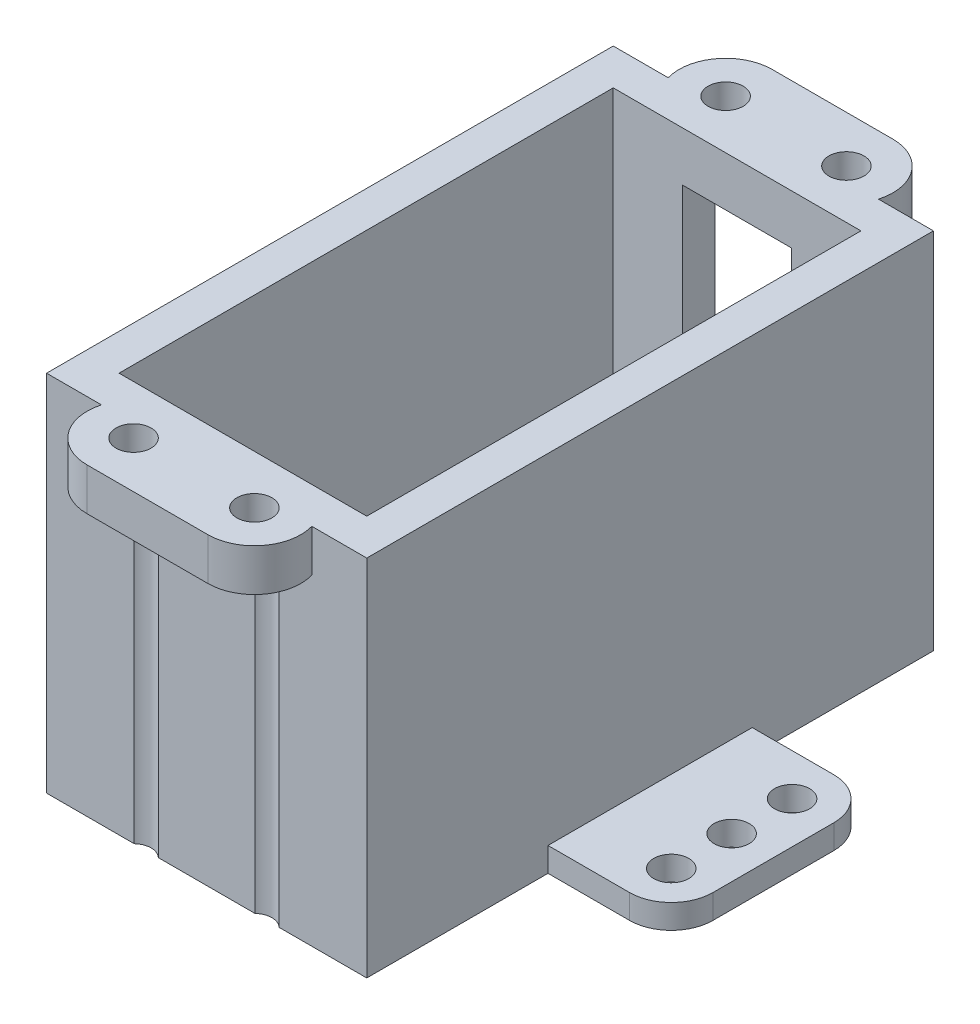
SolidWorks part; units mm, degrees
ref_plane "Alzado" through (0, 0, 0) normal (0, 0, 1) x (1, 0, 0)
ref_plane "Planta" through (0, 0, 0) normal (0, 1, 0) x (1, 0, 0)
ref_plane "Vista lateral" through (0, 0, 0) normal (1, 0, 0) x (0, 0, -1)
sketch "Croquis2" plane through (0, 0, 0) normal (0, 1, 0) x (1, 0, 0)
  line L0 (-10.8387, 0) -> (0, 0) construction
  line L1 (0, 5) -> (0, -5) construction
  line L2 (-23.45, 5) -> (-23.45, -5)
  line L3 (-13.25, -23.45) -> (13.25, -23.45)
  line L4 (-13.25, -23.45) -> (-13.25, -8.45)
  line L5 (-13.25, 23.45) -> (13.25, 23.45)
  line L6 (13.25, -23.45) -> (13.25, -8.45)
  line L7 (-13.25, -23.45) -> (13.25, 23.45) construction
  line L8 (-13.25, 23.45) -> (13.25, -23.45) construction
  line L9 (-20, -8.45) -> (-13.25, -8.45)
  line L10 (20, -8.45) -> (13.25, -8.45)
  line L11 (23.45, -5) -> (23.45, 5)
  line L12 (20, 8.45) -> (13.25, 8.45)
  line L13 (-20, 8.45) -> (-13.25, 8.45)
  line L14 (-13.25, 8.45) -> (-13.25, 23.45)
  line L15 (13.25, 8.45) -> (13.25, 23.45)
  circle A0 centre (-20, 5) radius 1.45
  circle A1 centre (-20, -5) radius 1.45
  circle A2 centre (20, -5) radius 1.45
  circle A3 centre (20, 5) radius 1.45
  arc A4 (-20, 8.45) -> (-23.45, 5) centre (-20, 5) ccw
  arc A5 (-20, -8.45) -> (-23.45, -5) centre (-20, -5) cw
  arc A6 (20, 8.45) -> (23.45, 5) centre (20, 5) cw
  arc A7 (20, -8.45) -> (23.45, -5) centre (20, -5) ccw
  circle A8 centre (-20, 0) radius 1.45
  circle A9 centre (-20, 5) radius 3.45 construction
  circle A10 centre (-20, -5) radius 3.45 construction
  circle A11 centre (20, 5) radius 3.45 construction
  circle A12 centre (20, -5) radius 3.45 construction
  circle A13 centre (20, 0) radius 1.45
  point P18 (-16.55, -5)
  point P20 (23.45, 5)
  point P22 (23.45, -5)
  point P37 (-16.55, 5)
  dimension "D1" = 2.9
  dimension "D2" = 5
  dimension "D3" = 20
  dimension "D7" = 2.9
  dimension "D8" = 20
  dimension "D4" = 26.5
  dimension "D5" = 46.9
  dimension "D6" = 2
extrude "Saliente-Extruir1" add sketch "Croquis2" along normal blind 2
sketch "Croquis3" plane through (0, 2, 0) normal (0, 1, 0) x (1, 0, 0)
  line L0 (-10.25, 20.45) -> (-10.25, -20.45)
  line L1 (-13.25, 23.45) -> (13.25, 23.45)
  line L2 (-13.25, 23.45) -> (-13.25, -23.45)
  line L3 (-13.25, -23.45) -> (13.25, -23.45)
  line L4 (13.25, 23.45) -> (13.25, -23.45)
  line L5 (-10.25, -20.45) -> (10.25, -20.45)
  line L6 (10.25, 20.45) -> (10.25, -20.45)
  line L7 (-10.25, 20.45) -> (10.25, 20.45)
  dimension "D1" = 3
extrude "Saliente-Extruir2" add sketch "Croquis3" along normal blind 28.1
sketch "Croquis4" plane through (0, 30.1, 0) normal (0, 1, 0) x (1, 0, 0)
  line L0 (0, 0) -> (0, 28.3845) construction
  line L1 (0, 0) -> (26.4868, 0) construction
  line L2 (-5, 28.3482) -> (5, 28.3482)
  line L4 (-8.7022, -23.45) -> (8.7022, -23.45)
  line L11 (-8.7022, 23.45) -> (8.7022, 23.45)
  line L12 (13.25, 23.45) -> (-13.25, 23.45) construction
  line L13 (-5, -28.3482) -> (5, -28.3482)
  circle A0 centre (-5, 24.5) radius 1.8482 construction
  arc A1 (-5, 28.3482) -> (-8.7022, 23.45) centre (-5, 24.5) ccw
  arc A2 (5, 28.3482) -> (8.7022, 23.45) centre (5, 24.5) cw
  circle A4 centre (-5, 24.5) radius 3.8482 construction
  arc A6 (-5, -28.3482) -> (-8.7022, -23.45) centre (-5, -24.5) cw
  arc A7 (5, -28.3482) -> (8.7022, -23.45) centre (5, -24.5) ccw
  point P18 (0.9482, 22.5)
  dimension "D1" = 5
  dimension "D2" = 24.5
  dimension "D3" = 2
extrude "Saliente-Extruir3" add sketch "Croquis4" against normal blind 3.5
sketch "Croquis5" plane through (0, 30.1, 0) normal (0, 1, 0) x (1, 0, 0)
  line L0 (0, 0) -> (26.4424, 0) construction
  line L1 (0, 0) -> (0, 31.0192) construction
  circle A0 centre (-5, 24.5) radius 1.45
  circle A1 centre (5, 24.5) radius 1.45
  circle A2 centre (5, -24.5) radius 1.45
  circle A3 centre (-5, -24.5) radius 1.45
  dimension "D1" = 2.9
extrude "Cortar-Extruir1" cut sketch "Croquis5" against normal through all
sketch "Croquis6" plane through (0, 0, -23.45) normal (0, 0, -1) x (-1, 0, 0)
  line L0 (-13.25, 2) -> (13.25, 2) construction
  line L1 (0, 0) -> (0, 36.2929) construction
  line L2 (-4.5, 2) -> (4.5, 2)
  line L3 (-4.5, 2) -> (-4.5, 26)
  line L4 (-4.5, 26) -> (4.5, 26)
  line L5 (4.5, 2) -> (4.5, 26)
  dimension "D1" = 9
  dimension "D2" = 4.5
  dimension "D3" = 24
extrude "Cortar-Extruir2" cut sketch "Croquis6" against normal blind 3.5
